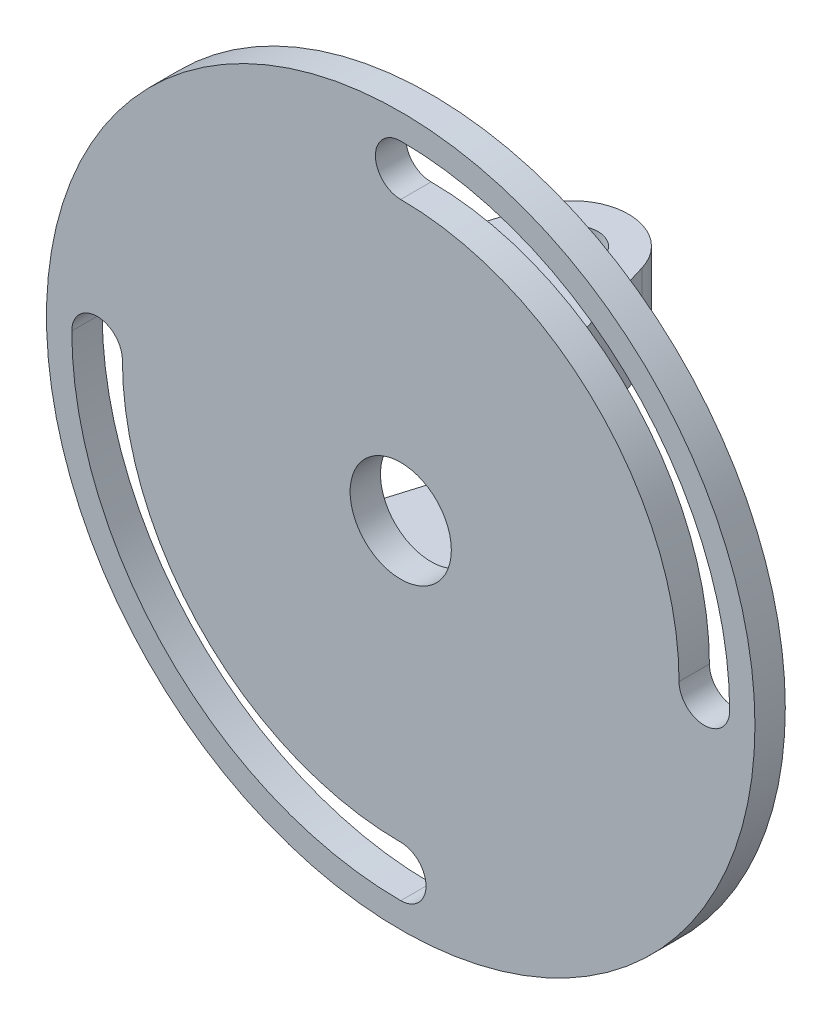
SolidWorks part; units mm, degrees
ref_plane "정면" through (0, 0, 0) normal (0, 0, 1) x (1, 0, 0)
ref_plane "윗면" through (0, 0, 0) normal (0, 1, 0) x (1, 0, 0)
ref_plane "우측면" through (0, 0, 0) normal (1, 0, 0) x (0, 0, -1)
sketch "스케치1" plane through (0, 0, 0) normal (0, 0, 1) x (1, 0, 0)
  line L0 (0, 65.3097) -> (0, -65.3097) construction
  line L1 (-109.2501, 0) -> (109.2501, 0) construction
  line L2 (15, 25.9808) -> (0, 0) construction
  circle A0 centre (0, 0) radius 5
  circle A1 centre (0, 0) radius 30 construction
  circle A2 centre (0, 0) radius 35
  circle A29 centre (0, 0) radius 32.5
  circle A30 centre (0, 0) radius 27.5
  circle A31 centre (30, 0) radius 2.5
  arc A32 (0, 32.5) -> (0, 27.5) centre (0, 30) ccw
  arc A33 (0, -32.5) -> (0, -27.5) centre (0, -30) cw
  circle A34 centre (-30, 0) radius 2.5
  circle A35 centre (0, -30) radius 2.5
  point P5 (0, 0)
  point P6 (0, 0)
  point P39 (0, 0)
  point P44 (0, 0)
  dimension "D1" = 10
  dimension "D2" = 60
  dimension "D3" = 70
  dimension "D4" = 65
  dimension "D7" = 55
  dimension "D8" = 2.5
  dimension "D6" = 30
sketch "스케치4" plane through (0, 0, 0) normal (1, 0, 0) x (0, 0, -1)
  line L0 (0, -6) -> (0, 6)
  line L1 (0, 65.3097) -> (0, -65.3097) construction
  line L5 (0, -6) -> (25, -6)
  line L6 (25, -6) -> (25, 6)
  line L7 (25, 6) -> (0, 6)
  point P4 (0, 0)
  dimension "D1" = 12
  dimension "D2" = 25
sketch "스케치5" plane through (0, 0, 0) normal (0, 1, 0) x (1, 0, 0)
  line L0 (-10, 0) -> (10, 0)
  line L1 (-109.2501, 0) -> (109.2501, 0) construction
  line L2 (0, 0) -> (0, 14) construction
  line L3 (-10, 0) -> (-5.2626, 15.5983)
  line L4 (10, 0) -> (5.2626, 15.5983)
  circle A0 centre (0, 14) radius 2.5
  arc A2 (-5.2626, 15.5983) -> (5.2626, 15.5983) centre (0, 14) cw
  point P4 (0, 0)
  dimension "D3" = 5
  dimension "D4" = 5.5
  dimension "D1" = 20
  dimension "D2" = 14
extrude "보스-돌출3" add sketch "스케치5" along normal mid plane 30
extrude "보스-돌출4" add sketch "스케치1" along normal blind 3 contours A2 A29 | A35 A29 A31 A30 | A30 A0 | A34 A30 A32 A29
extrude "컷-돌출1" cut sketch "스케치4" against normal through all both and the other way through all
